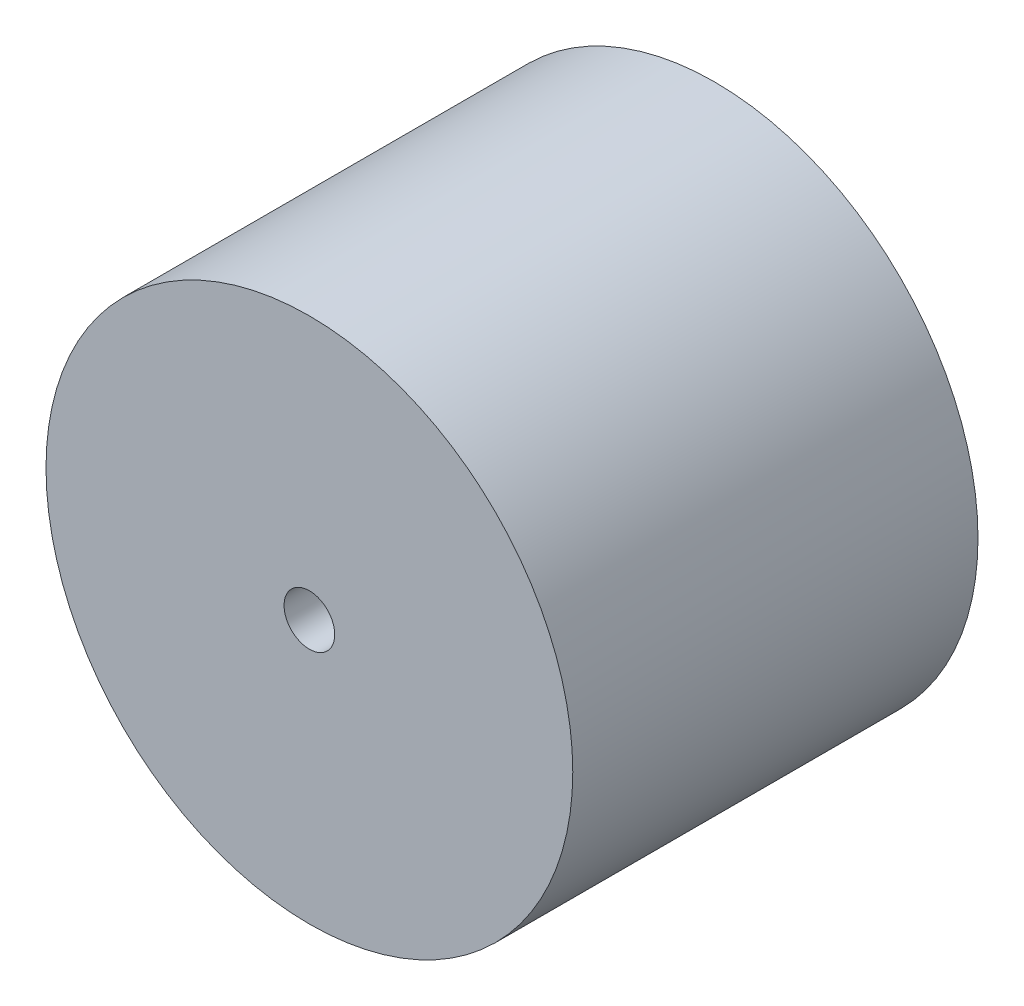
SolidWorks part; units mm, degrees
ref_plane "Front Plane" through (0, 0, 0) normal (0, 0, 1) x (1, 0, 0)
ref_plane "Top Plane" through (0, 0, 0) normal (0, 1, 0) x (1, 0, 0)
ref_plane "Right Plane" through (0, 0, 0) normal (1, 0, 0) x (0, 0, -1)
sketch "Sketch2" plane through (0, 0, 0) normal (0, 0, 1) x (1, 0, 0)
  circle A0 centre (0, 0) radius 16.51
  dimension "D1" = 33.02
extrude "Boss-Extrude1" add sketch "Sketch2" along normal blind 25.4
sketch "Sketch3" plane through (0, 0, 25.4) normal (0, 0, 1) x (1, 0, 0)
  circle A0 centre (0, 0) radius 1.5875
  dimension "D1" = 3.175
extrude "Cut-Extrude1" cut sketch "Sketch3" against normal through all
